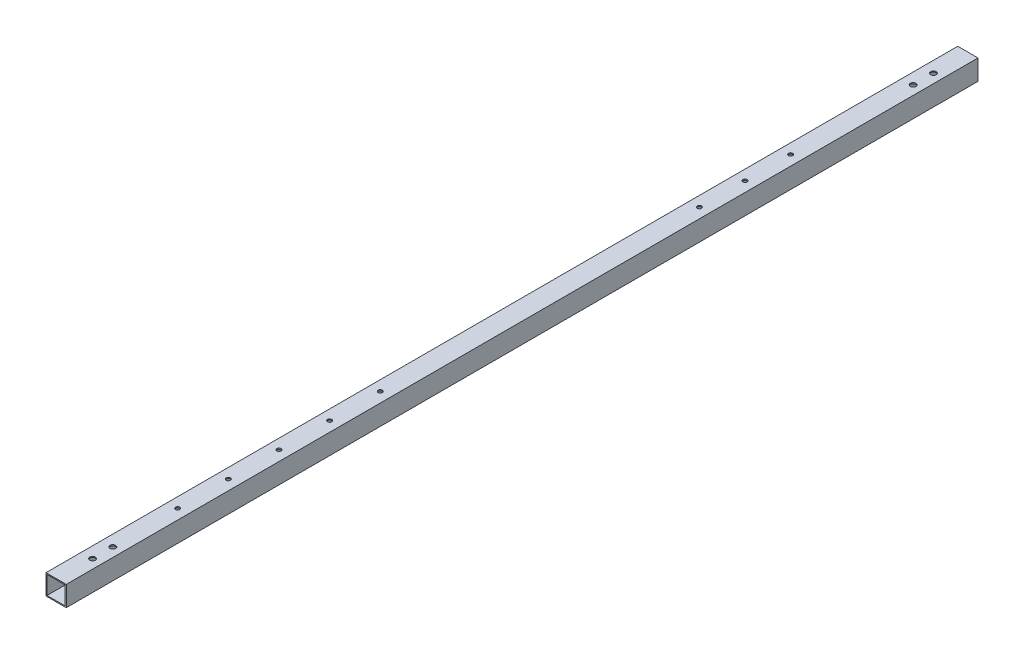
SolidWorks part; units mm, degrees
material "6061 合金"
ref_plane "前视基准面" through (0, 0, 0) normal (0, 0, 1) x (1, 0, 0)
ref_plane "上视基准面" through (0, 0, 0) normal (0, 1, 0) x (1, 0, 0)
ref_plane "右视基准面" through (0, 0, 0) normal (1, 0, 0) x (0, 0, -1)
other "Configuration Table"
sketch "草图1" plane through (0, 0, 0) normal (0, 0, 1) x (1, 0, 0)
  line L1 (0, 0) -> (20, 0)
  line L2 (0, 0) -> (0, -20)
  line L3 (0, -20) -> (20, -20)
  line L4 (20, 0) -> (20, -20)
  dimension "D1" = 20
extrude "拉伸-薄壁1" add sketch "草图1" along normal blind 900 thin
sketch "草图2" plane through (0, 0, 0) normal (0, 1, 0) x (1, 0, 0)
  line L0 (20, -900) -> (20, 0) construction
  line L1 (20, 0) -> (0, 0) construction
  line L2 (20, -450) -> (-658.8172, -450) construction
  circle A0 centre (11, -35) radius 2.75
  circle A1 centre (11, -55) radius 2.75
  circle A2 centre (11, -845) radius 2.75
  circle A3 centre (11, -865) radius 2.75
  dimension "D1" = 5.5
  dimension "D2" = 9
  dimension "D3" = 35
  dimension "D5" = 20
  dimension "D4" = 2
extrude "切除-拉伸1" cut sketch "草图2" against normal blind 37
sketch "草图3" plane through (0, 0, 0) normal (0, 1, 0) x (1, 0, 0)
  line L0 (20, -900) -> (20, 0) construction
  circle A0 centre (10, -175) radius 2.1
  circle A1 centre (11, -55) radius 2.75 construction
  circle A2 centre (10, -220) radius 2.1
  circle A3 centre (10, -265) radius 2.1
  dimension "D1" = 4.2
  dimension "D2" = 120
  dimension "D3" = 10
  dimension "D5" = 45
  dimension "D4" = 3
extrude "切除-拉伸2" cut sketch "草图3" against normal blind 37
sketch "草图4" plane through (0, 0, 0) normal (0, 1, 0) x (1, 0, 0)
  line L0 (10, -900) -> (10, -522.0411) construction
  line L1 (20, -900) -> (0, -900) construction
  line L6 (10, -700) -> (10, -322.0411) construction
  line L7 (10, -750) -> (10, -372.0411) construction
  line L8 (10, -800) -> (10, -422.0411) construction
  line L9 (10, -850) -> (10, -472.0411) construction
  circle A0 centre (10, -780) radius 2.1
  circle A1 centre (10, -730) radius 2.1
  circle A2 centre (10, -680) radius 2.1
  circle A3 centre (10, -630) radius 2.1
  circle A4 centre (10, -580) radius 2.1
  point P6 (10, -522.0411)
  dimension "D1" = 4.2
  dimension "D2" = 120
  dimension "D4" = 50
  dimension "D3" = 5
extrude "切除-拉伸3" cut sketch "草图4" against normal blind 37
